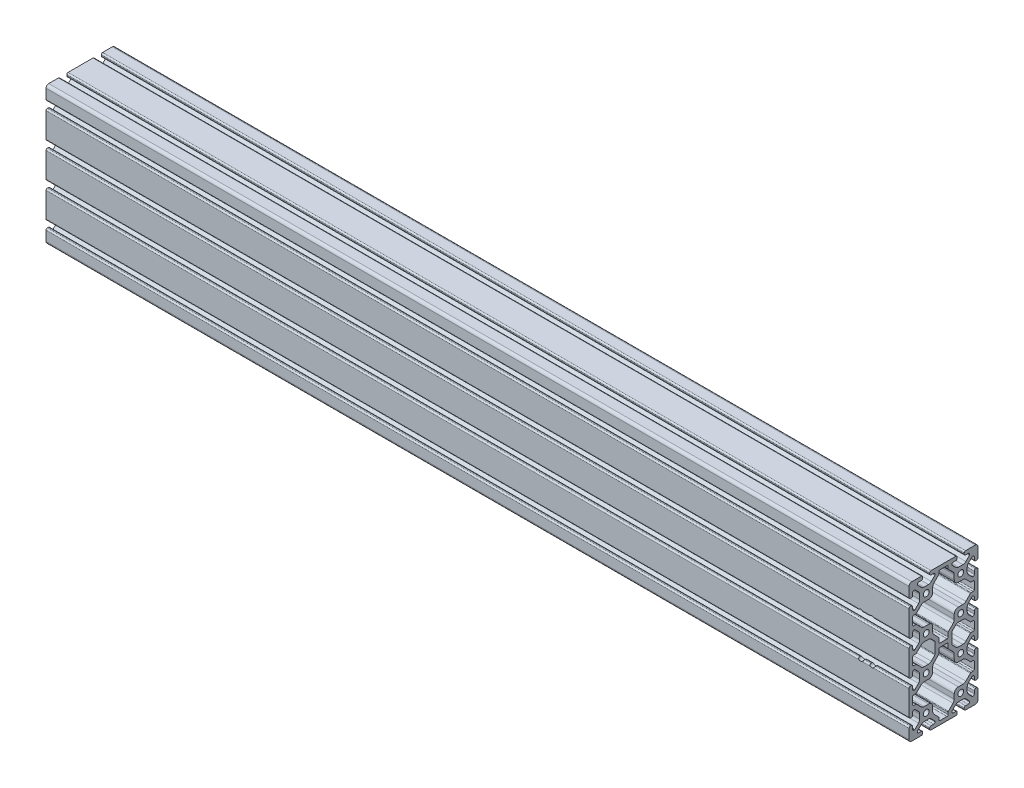
SolidWorks part; units mm, degrees
ref_plane "Front Plane" through (0, 0, 0) normal (0, 0, 1) x (1, 0, 0)
ref_plane "Top Plane" through (0, 0, 0) normal (0, 1, 0) x (1, 0, 0)
ref_plane "Right Plane" through (0, 0, 0) normal (1, 0, 0) x (0, 0, -1)
sketch "Sketch1" plane through (0, 0, 0) normal (0, 0, 1) x (1, 0, 0)
  line L0 (-500, 0) -> (500, 0)
  point P4 (0, 0)
  dimension "D1" = 1000
other "40 40-8016 PROFILE(1)"
ref_plane "Plane1" through (-500, 60, -20) normal (1, 0, 0) x (0, 0, 1)
sketch "Sketch11" plane through (-500, 60, -20) normal (1, 0, 0) x (0, 0, 1)
  line L0 (10.285, 66.1342) -> (10.285, 53.8658)
  line L1 (9.913, 52.9677) -> (5.8651, 48.9198)
  line L2 (2.5064, 47.5286) -> (-2.5064, 47.5286)
  line L3 (-5.8651, 48.9198) -> (-11.1783, 54.233)
  line L4 (-12.0763, 54.605) -> (-14.41, 54.605)
  line L5 (-15.68, 55.875) -> (-15.68, 64.125)
  line L6 (-14.41, 65.395) -> (-12.0763, 65.395)
  line L7 (-11.1783, 65.767) -> (-5.8651, 71.0802)
  line L8 (-2.5064, 72.4714) -> (2.5064, 72.4714)
  line L9 (5.8651, 71.0802) -> (9.913, 67.0323)
  line L10 (25.395, 67.9237) -> (25.395, 63.43)
  line L11 (24.125, 62.16) -> (15.875, 62.16)
  line L12 (14.605, 63.43) -> (14.605, 67.9237)
  line L13 (14.233, 68.8217) -> (8.9198, 74.1349)
  line L14 (7.5286, 77.4936) -> (7.5286, 82.7786)
  line L15 (2.7786, 87.5286) -> (-2.5064, 87.5286)
  line L16 (-5.8651, 88.9198) -> (-11.1783, 94.233)
  line L17 (-12.0763, 94.605) -> (-14.41, 94.605)
  line L18 (-15.68, 95.875) -> (-15.68, 104.125)
  line L19 (-14.41, 105.395) -> (-12.0763, 105.395)
  line L20 (-11.1783, 105.767) -> (-5.8651, 111.0802)
  line L21 (-2.5064, 112.4714) -> (2.7786, 112.4714)
  line L22 (7.5286, 117.2214) -> (7.5286, 122.5064)
  line L23 (8.9198, 125.8651) -> (14.233, 131.1783)
  line L24 (14.605, 132.0763) -> (14.605, 134.41)
  line L25 (15.875, 135.68) -> (24.125, 135.68)
  line L26 (25.395, 134.41) -> (25.395, 132.0763)
  line L27 (25.767, 131.1783) -> (31.0802, 125.8651)
  line L28 (32.4714, 122.5064) -> (32.4714, 117.2214)
  line L29 (37.2214, 112.4714) -> (42.5064, 112.4714)
  line L30 (45.8651, 111.0802) -> (51.1783, 105.767)
  line L31 (52.0763, 105.395) -> (54.41, 105.395)
  line L32 (55.68, 104.125) -> (55.68, 95.875)
  line L33 (54.41, 94.605) -> (52.0763, 94.605)
  line L34 (51.1783, 94.233) -> (45.8651, 88.9198)
  line L35 (42.5064, 87.5286) -> (37.2214, 87.5286)
  line L36 (32.4714, 82.7786) -> (32.4714, 77.4936)
  line L37 (31.0802, 74.1349) -> (25.767, 68.8217)
  line L38 (30.087, 67.0323) -> (34.1349, 71.0802)
  line L39 (37.4936, 72.4714) -> (42.5064, 72.4714)
  line L40 (45.8651, 71.0802) -> (51.1783, 65.767)
  line L41 (52.0763, 65.395) -> (54.41, 65.395)
  line L42 (55.68, 64.125) -> (55.68, 55.875)
  line L43 (54.41, 54.605) -> (52.0763, 54.605)
  line L44 (51.1783, 54.233) -> (45.8651, 48.9198)
  line L45 (42.5064, 47.5286) -> (37.4936, 47.5286)
  line L46 (34.1349, 48.9198) -> (30.087, 52.9677)
  line L47 (29.715, 53.8658) -> (29.715, 66.1342)
  line L48 (25.395, 56.57) -> (25.395, 52.0763)
  line L49 (25.767, 51.1783) -> (31.0802, 45.8651)
  line L50 (32.4714, 42.5064) -> (32.4714, 37.2214)
  line L51 (37.2214, 32.4714) -> (42.5064, 32.4714)
  line L52 (45.8651, 31.0802) -> (51.1783, 25.767)
  line L53 (52.0763, 25.395) -> (54.41, 25.395)
  line L54 (55.68, 24.125) -> (55.68, 15.875)
  line L55 (54.41, 14.605) -> (52.0763, 14.605)
  line L56 (51.1783, 14.233) -> (45.8651, 8.9198)
  line L57 (42.5064, 7.5286) -> (37.2214, 7.5286)
  line L58 (32.4714, 2.7786) -> (32.4714, -2.5064)
  line L59 (31.0802, -5.8651) -> (25.767, -11.1783)
  line L60 (25.395, -12.0763) -> (25.395, -14.41)
  line L61 (24.125, -15.68) -> (15.875, -15.68)
  line L62 (14.605, -14.41) -> (14.605, -12.0763)
  line L63 (14.233, -11.1783) -> (8.9198, -5.8651)
  line L64 (7.5286, -2.5064) -> (7.5286, 2.7786)
  line L65 (2.7786, 7.5286) -> (-2.5064, 7.5286)
  line L66 (-5.8651, 8.9198) -> (-11.1783, 14.233)
  line L67 (-12.0763, 14.605) -> (-14.41, 14.605)
  line L68 (-15.68, 15.875) -> (-15.68, 24.125)
  line L69 (-14.41, 25.395) -> (-12.0763, 25.395)
  line L70 (-11.1783, 25.767) -> (-5.8651, 31.0802)
  line L71 (-2.5064, 32.4714) -> (2.7786, 32.4714)
  line L72 (7.5286, 37.2214) -> (7.5286, 42.5064)
  line L73 (8.9198, 45.8651) -> (14.233, 51.1783)
  line L74 (14.605, 52.0763) -> (14.605, 56.57)
  line L75 (15.875, 57.84) -> (24.125, 57.84)
  line L76 (-18.43, 44.06) -> (-17.252, 44.06)
  line L77 (-15.682, 45.63) -> (-15.682, 48.715)
  line L78 (-14.112, 50.285) -> (-13.6545, 50.285)
  line L79 (-13.1171, 50.0624) -> (-8.9198, 45.8651)
  line L80 (-7.5286, 42.5064) -> (-7.5286, 37.4936)
  line L81 (-8.9198, 34.1349) -> (-13.1171, 29.9376)
  line L82 (-13.6545, 29.715) -> (-14.112, 29.715)
  line L83 (-15.682, 31.285) -> (-15.682, 34.37)
  line L84 (-17.252, 35.94) -> (-18.43, 35.94)
  line L85 (-20, 34.37) -> (-20, 5.63)
  line L86 (-18.43, 4.06) -> (-17.252, 4.06)
  line L87 (-15.682, 5.63) -> (-15.682, 8.715)
  line L88 (-14.112, 10.285) -> (-13.6545, 10.285)
  line L89 (-13.1171, 10.0624) -> (-8.9198, 5.8651)
  line L90 (-7.5286, 2.5064) -> (-7.5286, -2.5064)
  line L91 (-8.9198, -5.8651) -> (-13.1171, -10.0624)
  line L92 (-13.6545, -10.285) -> (-14.112, -10.285)
  line L93 (-15.682, -8.715) -> (-15.682, -5.63)
  line L94 (-17.252, -4.06) -> (-18.43, -4.06)
  line L95 (-20, -5.63) -> (-20, -16.83)
  line L96 (-16.83, -20) -> (-5.63, -20)
  line L97 (-4.06, -18.43) -> (-4.06, -17.252)
  line L98 (-5.63, -15.682) -> (-8.715, -15.682)
  line L99 (-10.285, -14.112) -> (-10.285, -13.6545)
  line L100 (-10.0624, -13.1171) -> (-5.8651, -8.9198)
  line L101 (-2.5064, -7.5286) -> (2.5064, -7.5286)
  line L102 (5.8651, -8.9198) -> (10.0624, -13.1171)
  line L103 (10.285, -13.6545) -> (10.285, -14.112)
  line L104 (8.715, -15.682) -> (5.63, -15.682)
  line L105 (4.06, -17.252) -> (4.06, -18.43)
  line L106 (5.63, -20) -> (34.37, -20)
  line L107 (35.94, -18.43) -> (35.94, -17.252)
  line L108 (34.37, -15.682) -> (31.285, -15.682)
  line L109 (29.715, -14.112) -> (29.715, -13.6545)
  line L110 (29.9376, -13.1171) -> (34.1349, -8.9198)
  line L111 (37.4936, -7.5286) -> (42.5064, -7.5286)
  line L112 (45.8651, -8.9198) -> (50.0624, -13.1171)
  line L113 (50.285, -13.6545) -> (50.285, -14.112)
  line L114 (48.715, -15.682) -> (45.63, -15.682)
  line L115 (44.06, -17.252) -> (44.06, -18.43)
  line L116 (45.63, -20) -> (56.83, -20)
  line L117 (60, -16.83) -> (60, -5.63)
  line L118 (58.43, -4.06) -> (57.252, -4.06)
  line L119 (55.682, -5.63) -> (55.682, -8.715)
  line L120 (54.112, -10.285) -> (53.6545, -10.285)
  line L121 (53.1171, -10.0624) -> (48.9198, -5.8651)
  line L122 (47.5286, -2.5064) -> (47.5286, 2.5064)
  line L123 (48.9198, 5.8651) -> (53.1171, 10.0624)
  line L124 (53.6545, 10.285) -> (54.112, 10.285)
  line L125 (55.682, 8.715) -> (55.682, 5.63)
  line L126 (57.252, 4.06) -> (58.43, 4.06)
  line L127 (60, 5.63) -> (60, 34.37)
  line L128 (58.43, 35.94) -> (57.252, 35.94)
  line L129 (55.682, 34.37) -> (55.682, 31.285)
  line L130 (54.112, 29.715) -> (53.6545, 29.715)
  line L131 (53.1171, 29.9376) -> (48.9198, 34.1349)
  line L132 (47.5286, 37.4936) -> (47.5286, 42.5064)
  line L133 (48.9198, 45.8651) -> (53.1171, 50.0624)
  line L134 (53.6545, 50.285) -> (54.112, 50.285)
  line L135 (55.682, 48.715) -> (55.682, 45.63)
  line L136 (57.252, 44.06) -> (58.43, 44.06)
  line L137 (60, 45.63) -> (60, 74.37)
  line L138 (58.43, 75.94) -> (57.252, 75.94)
  line L139 (55.682, 74.37) -> (55.682, 71.285)
  line L140 (54.112, 69.715) -> (53.6545, 69.715)
  line L141 (53.1171, 69.9376) -> (48.9198, 74.1349)
  line L142 (47.5286, 77.4936) -> (47.5286, 82.5064)
  line L143 (48.9198, 85.8651) -> (53.1171, 90.0624)
  line L144 (53.6545, 90.285) -> (54.112, 90.285)
  line L145 (55.682, 88.715) -> (55.682, 85.63)
  line L146 (57.252, 84.06) -> (58.43, 84.06)
  line L147 (60, 85.63) -> (60, 114.37)
  line L148 (58.43, 115.94) -> (57.252, 115.94)
  line L149 (55.682, 114.37) -> (55.682, 111.285)
  line L150 (54.112, 109.715) -> (53.6545, 109.715)
  line L151 (53.1171, 109.9376) -> (48.9198, 114.1349)
  line L152 (47.5286, 117.4936) -> (47.5286, 122.5064)
  line L153 (48.9198, 125.8651) -> (53.1171, 130.0624)
  line L154 (53.6545, 130.285) -> (54.112, 130.285)
  line L155 (55.682, 128.715) -> (55.682, 125.63)
  line L156 (57.252, 124.06) -> (58.43, 124.06)
  line L157 (60, 125.63) -> (60, 136.83)
  line L158 (56.83, 140) -> (45.63, 140)
  line L159 (44.06, 138.43) -> (44.06, 137.252)
  line L160 (45.63, 135.682) -> (48.715, 135.682)
  line L161 (50.285, 134.112) -> (50.285, 133.6545)
  line L162 (50.0624, 133.1171) -> (45.8651, 128.9198)
  line L163 (42.5064, 127.5286) -> (37.4936, 127.5286)
  line L164 (34.1349, 128.9198) -> (29.9376, 133.1171)
  line L165 (29.715, 133.6545) -> (29.715, 134.112)
  line L166 (31.285, 135.682) -> (34.37, 135.682)
  line L167 (35.94, 137.252) -> (35.94, 138.43)
  line L168 (34.37, 140) -> (5.63, 140)
  line L169 (4.06, 138.43) -> (4.06, 137.252)
  line L170 (5.63, 135.682) -> (8.715, 135.682)
  line L171 (10.285, 134.112) -> (10.285, 133.6545)
  line L172 (10.0624, 133.1171) -> (5.8651, 128.9198)
  line L173 (2.5064, 127.5286) -> (-2.5064, 127.5286)
  line L174 (-5.8651, 128.9198) -> (-10.0624, 133.1171)
  line L175 (-10.285, 133.6545) -> (-10.285, 134.112)
  line L176 (-8.715, 135.682) -> (-5.63, 135.682)
  line L177 (-4.06, 137.252) -> (-4.06, 138.43)
  line L178 (-5.63, 140) -> (-16.83, 140)
  line L179 (-20, 136.83) -> (-20, 125.63)
  line L180 (-18.43, 124.06) -> (-17.252, 124.06)
  line L181 (-15.682, 125.63) -> (-15.682, 128.715)
  line L182 (-14.112, 130.285) -> (-13.6545, 130.285)
  line L183 (-13.1171, 130.0624) -> (-8.9198, 125.8651)
  line L184 (-7.5286, 122.5064) -> (-7.5286, 117.4936)
  line L185 (-8.9198, 114.1349) -> (-13.1171, 109.9376)
  line L186 (-13.6545, 109.715) -> (-14.112, 109.715)
  line L187 (-15.682, 111.285) -> (-15.682, 114.37)
  line L188 (-17.252, 115.94) -> (-18.43, 115.94)
  line L189 (-20, 114.37) -> (-20, 85.63)
  line L190 (-18.43, 84.06) -> (-17.252, 84.06)
  line L191 (-15.682, 85.63) -> (-15.682, 88.715)
  line L192 (-14.112, 90.285) -> (-13.6545, 90.285)
  line L193 (-13.1171, 90.0624) -> (-8.9198, 85.8651)
  line L194 (-7.5286, 82.5064) -> (-7.5286, 77.4936)
  line L195 (-8.9198, 74.1349) -> (-13.1171, 69.9376)
  line L196 (-13.6545, 69.715) -> (-14.112, 69.715)
  line L197 (-15.682, 71.285) -> (-15.682, 74.37)
  line L198 (-17.252, 75.94) -> (-18.43, 75.94)
  line L199 (-20, 74.37) -> (-20, 45.63)
  arc A0 (9.913, 52.9677) -> (10.285, 53.8658) centre (9.015, 53.8658) ccw
  arc A1 (2.5064, 47.5286) -> (5.8651, 48.9198) centre (2.5064, 52.2786) ccw
  arc A2 (-5.8651, 48.9198) -> (-2.5064, 47.5286) centre (-2.5064, 52.2786) ccw
  arc A3 (-11.1783, 54.233) -> (-12.0763, 54.605) centre (-12.0763, 53.335) ccw
  arc A4 (-15.68, 55.875) -> (-14.41, 54.605) centre (-14.41, 55.875) ccw
  arc A5 (-14.41, 65.395) -> (-15.68, 64.125) centre (-14.41, 64.125) ccw
  arc A6 (-12.0763, 65.395) -> (-11.1783, 65.767) centre (-12.0763, 66.665) ccw
  arc A7 (-2.5064, 72.4714) -> (-5.8651, 71.0802) centre (-2.5064, 67.7214) ccw
  arc A8 (5.8651, 71.0802) -> (2.5064, 72.4714) centre (2.5064, 67.7214) ccw
  arc A9 (10.285, 66.1342) -> (9.913, 67.0323) centre (9.015, 66.1342) ccw
  arc A10 (24.125, 62.16) -> (25.395, 63.43) centre (24.125, 63.43) ccw
  arc A11 (14.605, 63.43) -> (15.875, 62.16) centre (15.875, 63.43) ccw
  arc A12 (14.605, 67.9237) -> (14.233, 68.8217) centre (13.335, 67.9237) ccw
  arc A13 (7.5286, 77.4936) -> (8.9198, 74.1349) centre (12.2786, 77.4936) ccw
  arc A14 (7.5286, 82.7786) -> (2.7786, 87.5286) centre (2.7786, 82.7786) ccw
  arc A15 (-5.8651, 88.9198) -> (-2.5064, 87.5286) centre (-2.5064, 92.2786) ccw
  arc A16 (-11.1783, 94.233) -> (-12.0763, 94.605) centre (-12.0763, 93.335) ccw
  arc A17 (-15.68, 95.875) -> (-14.41, 94.605) centre (-14.41, 95.875) ccw
  arc A18 (-14.41, 105.395) -> (-15.68, 104.125) centre (-14.41, 104.125) ccw
  arc A19 (-12.0763, 105.395) -> (-11.1783, 105.767) centre (-12.0763, 106.665) ccw
  arc A20 (-2.5064, 112.4714) -> (-5.8651, 111.0802) centre (-2.5064, 107.7214) ccw
  arc A21 (2.7786, 112.4714) -> (7.5286, 117.2214) centre (2.7786, 117.2214) ccw
  arc A22 (8.9198, 125.8651) -> (7.5286, 122.5064) centre (12.2786, 122.5064) ccw
  arc A23 (14.233, 131.1783) -> (14.605, 132.0763) centre (13.335, 132.0763) ccw
  arc A24 (15.875, 135.68) -> (14.605, 134.41) centre (15.875, 134.41) ccw
  arc A25 (25.395, 134.41) -> (24.125, 135.68) centre (24.125, 134.41) ccw
  arc A26 (25.395, 132.0763) -> (25.767, 131.1783) centre (26.665, 132.0763) ccw
  arc A27 (32.4714, 122.5064) -> (31.0802, 125.8651) centre (27.7214, 122.5064) ccw
  arc A28 (32.4714, 117.2214) -> (37.2214, 112.4714) centre (37.2214, 117.2214) ccw
  arc A29 (45.8651, 111.0802) -> (42.5064, 112.4714) centre (42.5064, 107.7214) ccw
  arc A30 (51.1783, 105.767) -> (52.0763, 105.395) centre (52.0763, 106.665) ccw
  arc A31 (55.68, 104.125) -> (54.41, 105.395) centre (54.41, 104.125) ccw
  arc A32 (54.41, 94.605) -> (55.68, 95.875) centre (54.41, 95.875) ccw
  arc A33 (52.0763, 94.605) -> (51.1783, 94.233) centre (52.0763, 93.335) ccw
  arc A34 (42.5064, 87.5286) -> (45.8651, 88.9198) centre (42.5064, 92.2786) ccw
  arc A35 (37.2214, 87.5286) -> (32.4714, 82.7786) centre (37.2214, 82.7786) ccw
  arc A36 (31.0802, 74.1349) -> (32.4714, 77.4936) centre (27.7214, 77.4936) ccw
  arc A37 (25.767, 68.8217) -> (25.395, 67.9237) centre (26.665, 67.9237) ccw
  arc A38 (30.087, 67.0323) -> (29.715, 66.1342) centre (30.985, 66.1342) ccw
  arc A39 (37.4936, 72.4714) -> (34.1349, 71.0802) centre (37.4936, 67.7214) ccw
  arc A40 (45.8651, 71.0802) -> (42.5064, 72.4714) centre (42.5064, 67.7214) ccw
  arc A41 (51.1783, 65.767) -> (52.0763, 65.395) centre (52.0763, 66.665) ccw
  arc A42 (55.68, 64.125) -> (54.41, 65.395) centre (54.41, 64.125) ccw
  arc A43 (54.41, 54.605) -> (55.68, 55.875) centre (54.41, 55.875) ccw
  arc A44 (52.0763, 54.605) -> (51.1783, 54.233) centre (52.0763, 53.335) ccw
  arc A45 (42.5064, 47.5286) -> (45.8651, 48.9198) centre (42.5064, 52.2786) ccw
  arc A46 (34.1349, 48.9198) -> (37.4936, 47.5286) centre (37.4936, 52.2786) ccw
  arc A47 (29.715, 53.8658) -> (30.087, 52.9677) centre (30.985, 53.8658) ccw
  arc A48 (25.395, 56.57) -> (24.125, 57.84) centre (24.125, 56.57) ccw
  arc A49 (25.395, 52.0763) -> (25.767, 51.1783) centre (26.665, 52.0763) ccw
  arc A50 (32.4714, 42.5064) -> (31.0802, 45.8651) centre (27.7214, 42.5064) ccw
  arc A51 (32.4714, 37.2214) -> (37.2214, 32.4714) centre (37.2214, 37.2214) ccw
  arc A52 (45.8651, 31.0802) -> (42.5064, 32.4714) centre (42.5064, 27.7214) ccw
  arc A53 (51.1783, 25.767) -> (52.0763, 25.395) centre (52.0763, 26.665) ccw
  arc A54 (55.68, 24.125) -> (54.41, 25.395) centre (54.41, 24.125) ccw
  arc A55 (54.41, 14.605) -> (55.68, 15.875) centre (54.41, 15.875) ccw
  arc A56 (52.0763, 14.605) -> (51.1783, 14.233) centre (52.0763, 13.335) ccw
  arc A57 (42.5064, 7.5286) -> (45.8651, 8.9198) centre (42.5064, 12.2786) ccw
  arc A58 (37.2214, 7.5286) -> (32.4714, 2.7786) centre (37.2214, 2.7786) ccw
  arc A59 (31.0802, -5.8651) -> (32.4714, -2.5064) centre (27.7214, -2.5064) ccw
  arc A60 (25.767, -11.1783) -> (25.395, -12.0763) centre (26.665, -12.0763) ccw
  arc A61 (24.125, -15.68) -> (25.395, -14.41) centre (24.125, -14.41) ccw
  arc A62 (14.605, -14.41) -> (15.875, -15.68) centre (15.875, -14.41) ccw
  arc A63 (14.605, -12.0763) -> (14.233, -11.1783) centre (13.335, -12.0763) ccw
  arc A64 (7.5286, -2.5064) -> (8.9198, -5.8651) centre (12.2786, -2.5064) ccw
  arc A65 (7.5286, 2.7786) -> (2.7786, 7.5286) centre (2.7786, 2.7786) ccw
  arc A66 (-5.8651, 8.9198) -> (-2.5064, 7.5286) centre (-2.5064, 12.2786) ccw
  arc A67 (-11.1783, 14.233) -> (-12.0763, 14.605) centre (-12.0763, 13.335) ccw
  arc A68 (-15.68, 15.875) -> (-14.41, 14.605) centre (-14.41, 15.875) ccw
  arc A69 (-14.41, 25.395) -> (-15.68, 24.125) centre (-14.41, 24.125) ccw
  arc A70 (-12.0763, 25.395) -> (-11.1783, 25.767) centre (-12.0763, 26.665) ccw
  arc A71 (-2.5064, 32.4714) -> (-5.8651, 31.0802) centre (-2.5064, 27.7214) ccw
  arc A72 (2.7786, 32.4714) -> (7.5286, 37.2214) centre (2.7786, 37.2214) ccw
  arc A73 (8.9198, 45.8651) -> (7.5286, 42.5064) centre (12.2786, 42.5064) ccw
  arc A74 (14.233, 51.1783) -> (14.605, 52.0763) centre (13.335, 52.0763) ccw
  arc A75 (15.875, 57.84) -> (14.605, 56.57) centre (15.875, 56.57) ccw
  circle A76 centre (40, 0) radius 3.4
  circle A77 centre (40, 40) radius 3.4
  circle A78 centre (0, 0) radius 3.4
  circle A79 centre (0, 40) radius 3.4
  circle A80 centre (40, 80) radius 3.4
  circle A81 centre (40, 120) radius 3.4
  circle A82 centre (0, 80) radius 3.4
  circle A83 centre (0, 120) radius 3.4
  arc A84 (-20, 45.63) -> (-18.43, 44.06) centre (-18.43, 45.63) ccw
  arc A85 (-17.252, 44.06) -> (-15.682, 45.63) centre (-17.252, 45.63) ccw
  arc A86 (-14.112, 50.285) -> (-15.682, 48.715) centre (-14.112, 48.715) ccw
  arc A87 (-13.1171, 50.0624) -> (-13.6545, 50.285) centre (-13.6545, 49.525) ccw
  arc A88 (-7.5286, 42.5064) -> (-8.9198, 45.8651) centre (-12.2786, 42.5064) ccw
  arc A89 (-8.9198, 34.1349) -> (-7.5286, 37.4936) centre (-12.2786, 37.4936) ccw
  arc A90 (-13.6545, 29.715) -> (-13.1171, 29.9376) centre (-13.6545, 30.475) ccw
  arc A91 (-15.682, 31.285) -> (-14.112, 29.715) centre (-14.112, 31.285) ccw
  arc A92 (-15.682, 34.37) -> (-17.252, 35.94) centre (-17.252, 34.37) ccw
  arc A93 (-18.43, 35.94) -> (-20, 34.37) centre (-18.43, 34.37) ccw
  arc A94 (-20, 5.63) -> (-18.43, 4.06) centre (-18.43, 5.63) ccw
  arc A95 (-17.252, 4.06) -> (-15.682, 5.63) centre (-17.252, 5.63) ccw
  arc A96 (-14.112, 10.285) -> (-15.682, 8.715) centre (-14.112, 8.715) ccw
  arc A97 (-13.1171, 10.0624) -> (-13.6545, 10.285) centre (-13.6545, 9.525) ccw
  arc A98 (-7.5286, 2.5064) -> (-8.9198, 5.8651) centre (-12.2786, 2.5064) ccw
  arc A99 (-8.9198, -5.8651) -> (-7.5286, -2.5064) centre (-12.2786, -2.5064) ccw
  arc A100 (-13.6545, -10.285) -> (-13.1171, -10.0624) centre (-13.6545, -9.525) ccw
  arc A101 (-15.682, -8.715) -> (-14.112, -10.285) centre (-14.112, -8.715) ccw
  arc A102 (-15.682, -5.63) -> (-17.252, -4.06) centre (-17.252, -5.63) ccw
  arc A103 (-18.43, -4.06) -> (-20, -5.63) centre (-18.43, -5.63) ccw
  arc A104 (-20, -16.83) -> (-16.83, -20) centre (-16.83, -16.83) ccw
  arc A105 (-5.63, -20) -> (-4.06, -18.43) centre (-5.63, -18.43) ccw
  arc A106 (-4.06, -17.252) -> (-5.63, -15.682) centre (-5.63, -17.252) ccw
  arc A107 (-10.285, -14.112) -> (-8.715, -15.682) centre (-8.715, -14.112) ccw
  arc A108 (-10.0624, -13.1171) -> (-10.285, -13.6545) centre (-9.525, -13.6545) ccw
  arc A109 (-2.5064, -7.5286) -> (-5.8651, -8.9198) centre (-2.5064, -12.2786) ccw
  arc A110 (5.8651, -8.9198) -> (2.5064, -7.5286) centre (2.5064, -12.2786) ccw
  arc A111 (10.285, -13.6545) -> (10.0624, -13.1171) centre (9.525, -13.6545) ccw
  arc A112 (8.715, -15.682) -> (10.285, -14.112) centre (8.715, -14.112) ccw
  arc A113 (5.63, -15.682) -> (4.06, -17.252) centre (5.63, -17.252) ccw
  arc A114 (4.06, -18.43) -> (5.63, -20) centre (5.63, -18.43) ccw
  arc A115 (34.37, -20) -> (35.94, -18.43) centre (34.37, -18.43) ccw
  arc A116 (35.94, -17.252) -> (34.37, -15.682) centre (34.37, -17.252) ccw
  arc A117 (29.715, -14.112) -> (31.285, -15.682) centre (31.285, -14.112) ccw
  arc A118 (29.9376, -13.1171) -> (29.715, -13.6545) centre (30.475, -13.6545) ccw
  arc A119 (37.4936, -7.5286) -> (34.1349, -8.9198) centre (37.4936, -12.2786) ccw
  arc A120 (45.8651, -8.9198) -> (42.5064, -7.5286) centre (42.5064, -12.2786) ccw
  arc A121 (50.285, -13.6545) -> (50.0624, -13.1171) centre (49.525, -13.6545) ccw
  arc A122 (48.715, -15.682) -> (50.285, -14.112) centre (48.715, -14.112) ccw
  arc A123 (45.63, -15.682) -> (44.06, -17.252) centre (45.63, -17.252) ccw
  arc A124 (44.06, -18.43) -> (45.63, -20) centre (45.63, -18.43) ccw
  arc A125 (56.83, -20) -> (60, -16.83) centre (56.83, -16.83) ccw
  arc A126 (60, -5.63) -> (58.43, -4.06) centre (58.43, -5.63) ccw
  arc A127 (57.252, -4.06) -> (55.682, -5.63) centre (57.252, -5.63) ccw
  arc A128 (54.112, -10.285) -> (55.682, -8.715) centre (54.112, -8.715) ccw
  arc A129 (53.1171, -10.0624) -> (53.6545, -10.285) centre (53.6545, -9.525) ccw
  arc A130 (47.5286, -2.5064) -> (48.9198, -5.8651) centre (52.2786, -2.5064) ccw
  arc A131 (48.9198, 5.8651) -> (47.5286, 2.5064) centre (52.2786, 2.5064) ccw
  arc A132 (53.6545, 10.285) -> (53.1171, 10.0624) centre (53.6545, 9.525) ccw
  arc A133 (55.682, 8.715) -> (54.112, 10.285) centre (54.112, 8.715) ccw
  arc A134 (55.682, 5.63) -> (57.252, 4.06) centre (57.252, 5.63) ccw
  arc A135 (58.43, 4.06) -> (60, 5.63) centre (58.43, 5.63) ccw
  arc A136 (60, 34.37) -> (58.43, 35.94) centre (58.43, 34.37) ccw
  arc A137 (57.252, 35.94) -> (55.682, 34.37) centre (57.252, 34.37) ccw
  arc A138 (54.112, 29.715) -> (55.682, 31.285) centre (54.112, 31.285) ccw
  arc A139 (53.1171, 29.9376) -> (53.6545, 29.715) centre (53.6545, 30.475) ccw
  arc A140 (47.5286, 37.4936) -> (48.9198, 34.1349) centre (52.2786, 37.4936) ccw
  arc A141 (48.9198, 45.8651) -> (47.5286, 42.5064) centre (52.2786, 42.5064) ccw
  arc A142 (53.6545, 50.285) -> (53.1171, 50.0624) centre (53.6545, 49.525) ccw
  arc A143 (55.682, 48.715) -> (54.112, 50.285) centre (54.112, 48.715) ccw
  arc A144 (55.682, 45.63) -> (57.252, 44.06) centre (57.252, 45.63) ccw
  arc A145 (58.43, 44.06) -> (60, 45.63) centre (58.43, 45.63) ccw
  arc A146 (60, 74.37) -> (58.43, 75.94) centre (58.43, 74.37) ccw
  arc A147 (57.252, 75.94) -> (55.682, 74.37) centre (57.252, 74.37) ccw
  arc A148 (54.112, 69.715) -> (55.682, 71.285) centre (54.112, 71.285) ccw
  arc A149 (53.1171, 69.9376) -> (53.6545, 69.715) centre (53.6545, 70.475) ccw
  arc A150 (47.5286, 77.4936) -> (48.9198, 74.1349) centre (52.2786, 77.4936) ccw
  arc A151 (48.9198, 85.8651) -> (47.5286, 82.5064) centre (52.2786, 82.5064) ccw
  arc A152 (53.6545, 90.285) -> (53.1171, 90.0624) centre (53.6545, 89.525) ccw
  arc A153 (55.682, 88.715) -> (54.112, 90.285) centre (54.112, 88.715) ccw
  arc A154 (55.682, 85.63) -> (57.252, 84.06) centre (57.252, 85.63) ccw
  arc A155 (58.43, 84.06) -> (60, 85.63) centre (58.43, 85.63) ccw
  arc A156 (60, 114.37) -> (58.43, 115.94) centre (58.43, 114.37) ccw
  arc A157 (57.252, 115.94) -> (55.682, 114.37) centre (57.252, 114.37) ccw
  arc A158 (54.112, 109.715) -> (55.682, 111.285) centre (54.112, 111.285) ccw
  arc A159 (53.1171, 109.9376) -> (53.6545, 109.715) centre (53.6545, 110.475) ccw
  arc A160 (47.5286, 117.4936) -> (48.9198, 114.1349) centre (52.2786, 117.4936) ccw
  arc A161 (48.9198, 125.8651) -> (47.5286, 122.5064) centre (52.2786, 122.5064) ccw
  arc A162 (53.6545, 130.285) -> (53.1171, 130.0624) centre (53.6545, 129.525) ccw
  arc A163 (55.682, 128.715) -> (54.112, 130.285) centre (54.112, 128.715) ccw
  arc A164 (55.682, 125.63) -> (57.252, 124.06) centre (57.252, 125.63) ccw
  arc A165 (58.43, 124.06) -> (60, 125.63) centre (58.43, 125.63) ccw
  arc A166 (60, 136.83) -> (56.83, 140) centre (56.83, 136.83) ccw
  arc A167 (45.63, 140) -> (44.06, 138.43) centre (45.63, 138.43) ccw
  arc A168 (44.06, 137.252) -> (45.63, 135.682) centre (45.63, 137.252) ccw
  arc A169 (50.285, 134.112) -> (48.715, 135.682) centre (48.715, 134.112) ccw
  arc A170 (50.0624, 133.1171) -> (50.285, 133.6545) centre (49.525, 133.6545) ccw
  arc A171 (42.5064, 127.5286) -> (45.8651, 128.9198) centre (42.5064, 132.2786) ccw
  arc A172 (34.1349, 128.9198) -> (37.4936, 127.5286) centre (37.4936, 132.2786) ccw
  arc A173 (29.715, 133.6545) -> (29.9376, 133.1171) centre (30.475, 133.6545) ccw
  arc A174 (31.285, 135.682) -> (29.715, 134.112) centre (31.285, 134.112) ccw
  arc A175 (34.37, 135.682) -> (35.94, 137.252) centre (34.37, 137.252) ccw
  arc A176 (35.94, 138.43) -> (34.37, 140) centre (34.37, 138.43) ccw
  arc A177 (5.63, 140) -> (4.06, 138.43) centre (5.63, 138.43) ccw
  arc A178 (4.06, 137.252) -> (5.63, 135.682) centre (5.63, 137.252) ccw
  arc A179 (10.285, 134.112) -> (8.715, 135.682) centre (8.715, 134.112) ccw
  arc A180 (10.0624, 133.1171) -> (10.285, 133.6545) centre (9.525, 133.6545) ccw
  arc A181 (2.5064, 127.5286) -> (5.8651, 128.9198) centre (2.5064, 132.2786) ccw
  arc A182 (-5.8651, 128.9198) -> (-2.5064, 127.5286) centre (-2.5064, 132.2786) ccw
  arc A183 (-10.285, 133.6545) -> (-10.0624, 133.1171) centre (-9.525, 133.6545) ccw
  arc A184 (-8.715, 135.682) -> (-10.285, 134.112) centre (-8.715, 134.112) ccw
  arc A185 (-5.63, 135.682) -> (-4.06, 137.252) centre (-5.63, 137.252) ccw
  arc A186 (-4.06, 138.43) -> (-5.63, 140) centre (-5.63, 138.43) ccw
  arc A187 (-16.83, 140) -> (-20, 136.83) centre (-16.83, 136.83) ccw
  arc A188 (-20, 125.63) -> (-18.43, 124.06) centre (-18.43, 125.63) ccw
  arc A189 (-17.252, 124.06) -> (-15.682, 125.63) centre (-17.252, 125.63) ccw
  arc A190 (-14.112, 130.285) -> (-15.682, 128.715) centre (-14.112, 128.715) ccw
  arc A191 (-13.1171, 130.0624) -> (-13.6545, 130.285) centre (-13.6545, 129.525) ccw
  arc A192 (-7.5286, 122.5064) -> (-8.9198, 125.8651) centre (-12.2786, 122.5064) ccw
  arc A193 (-8.9198, 114.1349) -> (-7.5286, 117.4936) centre (-12.2786, 117.4936) ccw
  arc A194 (-13.6545, 109.715) -> (-13.1171, 109.9376) centre (-13.6545, 110.475) ccw
  arc A195 (-15.682, 111.285) -> (-14.112, 109.715) centre (-14.112, 111.285) ccw
  arc A196 (-15.682, 114.37) -> (-17.252, 115.94) centre (-17.252, 114.37) ccw
  arc A197 (-18.43, 115.94) -> (-20, 114.37) centre (-18.43, 114.37) ccw
  arc A198 (-20, 85.63) -> (-18.43, 84.06) centre (-18.43, 85.63) ccw
  arc A199 (-17.252, 84.06) -> (-15.682, 85.63) centre (-17.252, 85.63) ccw
  arc A200 (-14.112, 90.285) -> (-15.682, 88.715) centre (-14.112, 88.715) ccw
  arc A201 (-13.1171, 90.0624) -> (-13.6545, 90.285) centre (-13.6545, 89.525) ccw
  arc A202 (-7.5286, 82.5064) -> (-8.9198, 85.8651) centre (-12.2786, 82.5064) ccw
  arc A203 (-8.9198, 74.1349) -> (-7.5286, 77.4936) centre (-12.2786, 77.4936) ccw
  arc A204 (-13.6545, 69.715) -> (-13.1171, 69.9376) centre (-13.6545, 70.475) ccw
  arc A205 (-15.682, 71.285) -> (-14.112, 69.715) centre (-14.112, 71.285) ccw
  arc A206 (-15.682, 74.37) -> (-17.252, 75.94) centre (-17.252, 74.37) ccw
  arc A207 (-18.43, 75.94) -> (-20, 74.37) centre (-18.43, 74.37) ccw
  point P0 (-20, 140)
  point P1 (0, 140)
  point P2 (20, 140)
  point P619 (40, 140)
  point P620 (60, 140)
  point P621 (60, 120)
  point P622 (20, 120)
  point P623 (-20, 120)
  point P624 (0, 120)
  point P625 (40, 120)
  point P626 (-20, 100)
  point P627 (0, 100)
  point P628 (20, 100)
  point P629 (40, 100)
  point P630 (60, 100)
  point P631 (60, 80)
  point P632 (40, 80)
  point P633 (20, 80)
  point P634 (0, 80)
  point P635 (-20, 80)
  point P636 (-20, 60)
  point P637 (0, 60)
  point P638 (20, 60)
  point P639 (40, 60)
  point P640 (60, 60)
  point P641 (60, 40)
  point P642 (40, 40)
  point P643 (20, 40)
  point P644 (0, 40)
  point P645 (-20, 40)
  point P646 (-20, 20)
  point P647 (0, 20)
  point P648 (20, 20)
  point P649 (40, 20)
  point P650 (60, 20)
  point P651 (60, 0)
  point P652 (60, -20)
  point P653 (40, -20)
  point P654 (40, 0)
  point P655 (20, -20)
  point P656 (20, 0)
  point P657 (0, -20)
  point P658 (-20, -20)
  point P659 (-20, 0)
  point P660 (0, 0)
sketch "Sketch12" plane through (0, 0, 40) normal (0, 0, 1) x (1, 0, 0)
  line L0 (-500, 0) -> (500, 0) construction
  line L1 (444, -23) -> (457, -23) construction
  line L2 (444, -23) -> (444, 23) construction
  line L3 (444, 23) -> (457, 23) construction
  line L4 (457, -23) -> (457, 23) construction
  line L5 (450.5, 23) -> (450.5, -23) construction
  line L6 (444, 0) -> (457, 0) construction
  circle A0 centre (457, 23) radius 3.1
  circle A1 centre (444, 23) radius 3.1
  circle A2 centre (444, -23) radius 3.1
  circle A3 centre (457, -23) radius 3.1
  point P0 (450.5, 0)
  dimension "D4" = 6.2
  dimension "D1" = 13
  dimension "D2" = 46
  dimension "D3" = 43
hole_wizard "M6x1.0 Tapped Hole1" positions "Sketch13" profile "Sketch14" tap size "M6x1.0" standard "ANSI Metric"
sketch "Sketch13" plane through (0, 0, 40) normal (0, 0, 1) x (1, 0, 0)
  point P0 (457, 23)
  point P3 (444, 23)
  point P6 (457, -23)
  point P9 (444, -23)
sketch "Sketch14" plane through (457, 23, 40) normal (1, 0, 0) x (0, -1, 0)
  line L0 (0, 0) -> (0, 31.5022)
  line L1 (0, 31.5022) -> (2.5, 30)
  line L2 (2.5, 30) -> (2.5, 0.525)
  line L3 (2.5, 0.525) -> (3.025, 0)
  line L5 (3.025, 0) -> (0, 0)
  line L6 (-2.5, 0.525) -> (-3.025, 0) construction
  line L10 (0, 31.5022) -> (-2.5, 30) construction
  line L11 (0, -6.35) -> (0, 107.95) construction
  dimension "Tap Drill Dia." = 5
  dimension "Tap Drill Depth" = 30
  dimension "Near C'Sink Dia." = 6.05
  dimension "Near C'Sink Angle" = 90
  dimension "Drill Angle" = 118
cosmetic thread "Hole Thread9" parameters "D1"=12, "D2"=6
cosmetic thread "Hole Thread10" parameters "D1"=12, "D2"=6
cosmetic thread "Hole Thread11" parameters "D1"=12, "D2"=6
cosmetic thread "Hole Thread12" parameters "D1"=12, "D2"=6
extrude "Cut-Extrude1" cut sketch "Sketch12" against normal up to surface (4.318 mm away) up to face at (0, 27.1725, 35.682)
ref_plane "Plane2" through (0, 60, 0) normal (0, 1, 0) x (1, 0, 0)
ref_plane "Plane3" through (0, -60, 0) normal (0, 1, 0) x (1, 0, 0)
